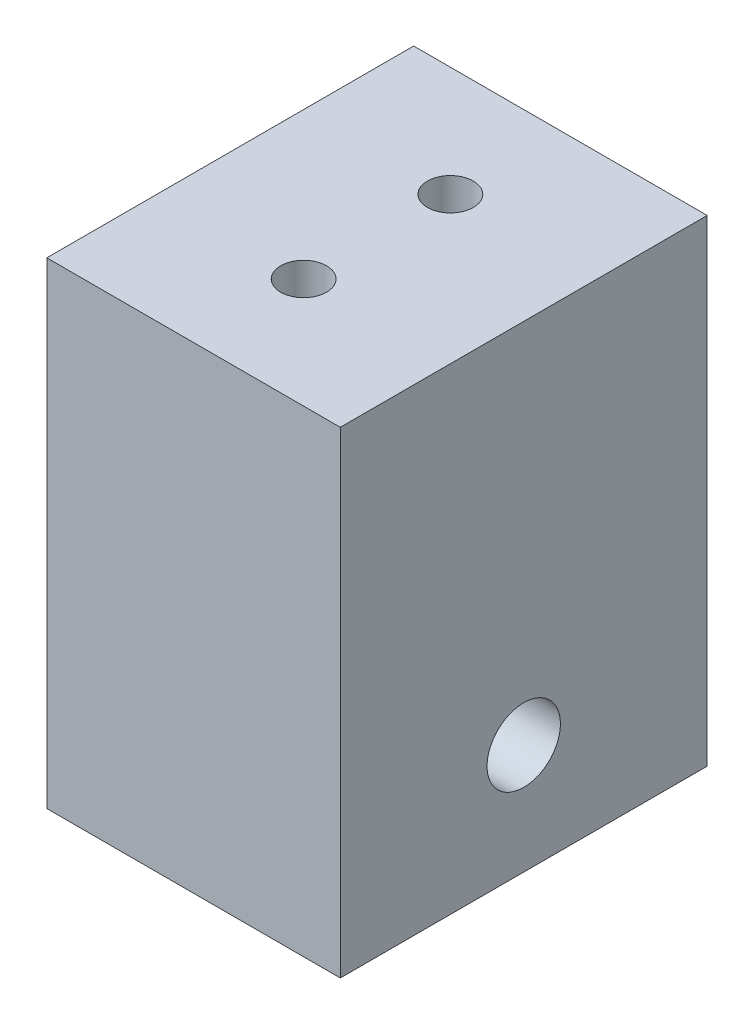
SolidWorks part; units mm, degrees
material "6061 Alloy"
ref_plane "Front Plane" through (0, 0, 0) normal (0, 0, 1) x (1, 0, 0)
ref_plane "Top Plane" through (0, 0, 0) normal (0, 1, 0) x (1, 0, 0)
ref_plane "Right Plane" through (0, 0, 0) normal (1, 0, 0) x (0, 0, -1)
sketch "Sketch1" plane through (0, 0, 0) normal (0, 1, 0) x (1, 0, 0)
  line L1 (-12.7, -15.875) -> (12.7, -15.875)
  line L2 (-12.7, -15.875) -> (-12.7, 15.875)
  line L3 (-12.7, 15.875) -> (12.7, 15.875)
  line L4 (12.7, -15.875) -> (12.7, 15.875)
  line L5 (-12.7, -15.875) -> (12.7, 15.875) construction
  line L6 (-12.7, 15.875) -> (12.7, -15.875) construction
  point P0 (0, 0)
  dimension "D1" = 25.4
  dimension "D2" = 31.75
extrude "Boss-Extrude1" add sketch "Sketch1" along normal blind 41.275
sketch "Sketch2" plane through (12.7, 0, 0) normal (1, 0, 0) x (0, 0, -1)
  line L0 (-15.875, 0) -> (15.875, 0) construction
  circle A0 centre (0, 9.525) radius 3.175
  dimension "D2" = 6.35
  dimension "D1" = 9.525
extrude "1/4\" Through Hole" cut sketch "Sketch2" against normal through all
sketch "Sketch3" plane through (0, 41.275, 0) normal (0, 1, 0) x (1, 0, 0)
  circle A0 centre (0, 6.35) radius 1.9844
  circle A1 centre (0, -6.35) radius 1.9844
  dimension "D3" = 3.9688
  dimension "D1" = 6.35
  dimension "D2" = 6.35
extrude "10-32 Threaded Holes (1\")" cut sketch "Sketch3" against normal blind 25.4
